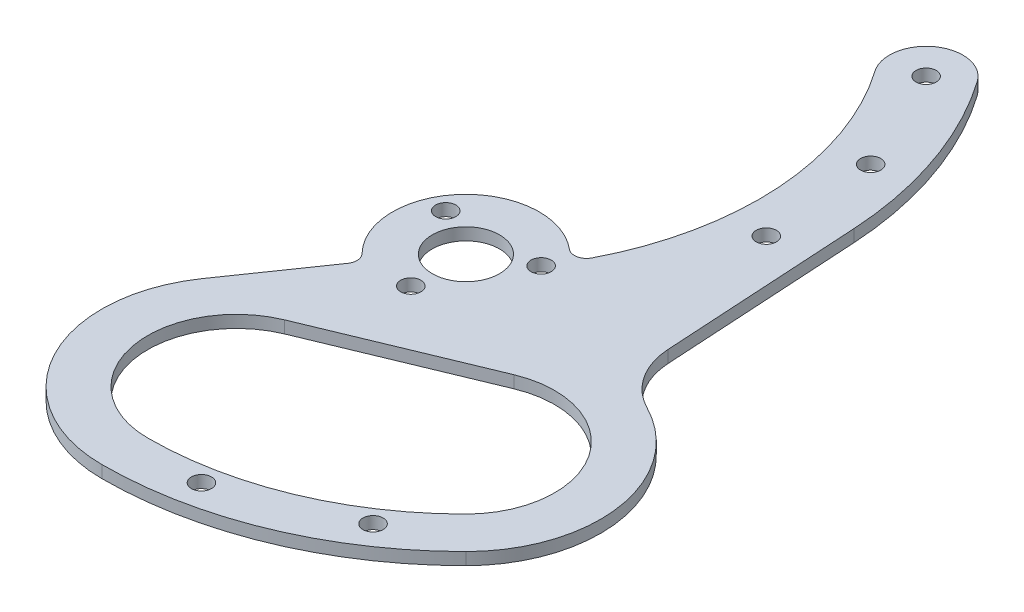
SolidWorks part; units mm, degrees
ref_plane "Спереди" through (0, 0, 0) normal (0, 0, 1) x (1, 0, 0)
ref_plane "Сверху" through (0, 0, 0) normal (0, 1, 0) x (1, 0, 0)
ref_plane "Справа" through (0, 0, 0) normal (1, 0, 0) x (0, 0, -1)
sketch "Эскиз1" plane through (0, 0, 0) normal (0, 1, 0) x (1, 0, 0)
  line L0 (0, -52) -> (0, -59.5) construction
  line L1 (36.7696, -36.7696) -> (42.0729, -42.0729) construction
  line L2 (0, -52) -> (0, 0) construction
  line L3 (0, 0) -> (0, 63.6396) construction
  line L4 (-31.8198, 31.8198) -> (0, 63.6396) construction
  line L5 (-7.3581, -9.4794) -> (-18.0878, -24.9768)
  line L6 (0, 0) -> (36.7696, -36.7696) construction
  line L7 (19.8995, -48.0417) -> (22.7697, -54.9708) construction
  line L8 (0, 0) -> (-7.7942, 4.5) construction
  line L9 (-18.0878, -24.9768) -> (30.4512, -4.8712) construction
  line L10 (0, 0) -> (7.7942, 4.5) construction
  line L11 (-31.8198, 31.8198) -> (0, 0) construction
  line L12 (-5.5489, -24.1037) -> (20.9676, -13.1203)
  line L13 (30.4512, -4.8712) -> (28.0759, 35.3565)
  line L14 (-31.8198, 31.8198) -> (0, 63.6396) construction
  line L15 (28.1802, 31.8198) -> (16.1802, 31.8198) construction
  line L18 (-31.8198, 31.8198) -> (17.3293, 66.2344) construction
  arc A0 (42.0729, -42.0729) -> (0, -59.5) centre (0, 0) cw
  arc A1 (0, -52) -> (36.7696, -36.7696) centre (0, 0) ccw
  arc A2 (0, -54.9973) -> (21.0466, -50.8109) centre (0, 0) ccw construction
  circle A3 centre (10.7294, -53.9406) radius 1.65
  circle A4 centre (30.5549, -45.7286) radius 1.65
  arc A5 (7.4995, 59.3515) -> (9.4794, 7.3581) centre (-31.8198, 31.8198) cw
  circle A6 centre (0, 0) radius 5.5
  arc A7 (17.3293, 66.2344) -> (28.0759, 35.3565) centre (-31.8198, 31.8198) cw
  arc A8 (22.1802, 31.8198) -> (12.4144, 62.7929) centre (-31.8198, 31.8198) ccw construction
  arc A9 (7.4995, 59.3515) -> (17.3293, 66.2344) centre (12.4144, 62.7929) cw
  arc A10 (9.4794, 7.3581) -> (-7.3581, -9.4794) centre (-31.8198, 31.8198) cw construction
  arc A11 (36.7696, -36.7696) -> (20.9676, -13.1203) centre (26.5165, -26.5165) ccw
  circle A13 centre (0, 0) radius 9 construction
  circle A14 centre (0, -9) radius 1.65
  circle A15 centre (-7.7942, 4.5) radius 1.65
  arc A16 (42.0729, -42.0729) -> (30.4512, -4.8712) centre (26.5165, -26.5165) ccw
  arc A18 (0, -52) -> (-5.5489, -24.1037) centre (0, -37.5) cw
  circle A19 centre (7.7942, 4.5) radius 1.65
  arc A20 (0, 0) -> (-4.1195, -3.6442) centre (-31.8198, 31.8198) ccw construction
  arc A22 (9.4794, 7.3581) -> (-7.3581, -9.4794) centre (0, 0) ccw
  arc A23 (0, -59.5) -> (-18.0878, -24.9768) centre (0, -37.5) cw
  point P1 (22.1802, 31.8198)
  point P45 (10.7294, -53.9406)
  dimension "D3" = 52
  dimension "D4" = 3.3
  dimension "D7" = 90
  dimension "D8" = 120
  dimension "D9" = 11
  dimension "D10" = 90
  dimension "D11" = 18
  dimension "D12" = 48
  dimension "D14" = 60
  dimension "D20" = 22
  dimension "D16" = 29
  dimension "D17" = 12
  dimension "D18" = 10
  dimension "D5" = 54.9973
  dimension "D6" = 45
  dimension "D15" = 120
extrude "Бобышка-Вытянуть1" add sketch "Эскиз1" along normal blind 2
sketch "Эскиз2" plane through (0, 0, 0) normal (0, -1, 0) x (1, 0, 0)
  line L0 (-31.8198, -31.8198) -> (0, 0) construction
  line L1 (-31.8198, -31.8198) -> (22.9872, -27.0248) construction
  line L2 (-31.8198, -31.8198) -> (13.7419, -63.7224) construction
  line L3 (-31.8198, -31.8198) -> (22.5978, -46.401) construction
  circle A0 centre (21.9747, -27.1134) radius 1.65
  circle A1 centre (12.4144, -62.7929) radius 1.65
  circle A2 centre (20.3402, -45.796) radius 1.65
  circle A3 centre (-31.8198, -31.8198) radius 54 construction
  point P0 (-31.8198, -31.8198)
  dimension "D3" = 3.3
  dimension "D4" = 3.3
  dimension "D5" = 3.3
  dimension "D1" = 40
  dimension "D2" = 60
  dimension "D6" = 80
extrude "Вырез-Вытянуть1" cut sketch "Эскиз2" against normal through all
fillet "Скругление1" radius 2 2 edges at (9.4794, 1, -7.3581) (-7.3581, 1, 9.4794)
fillet "Скругление2" radius 12 1 edges at (30.4512, 1, 4.8712)
